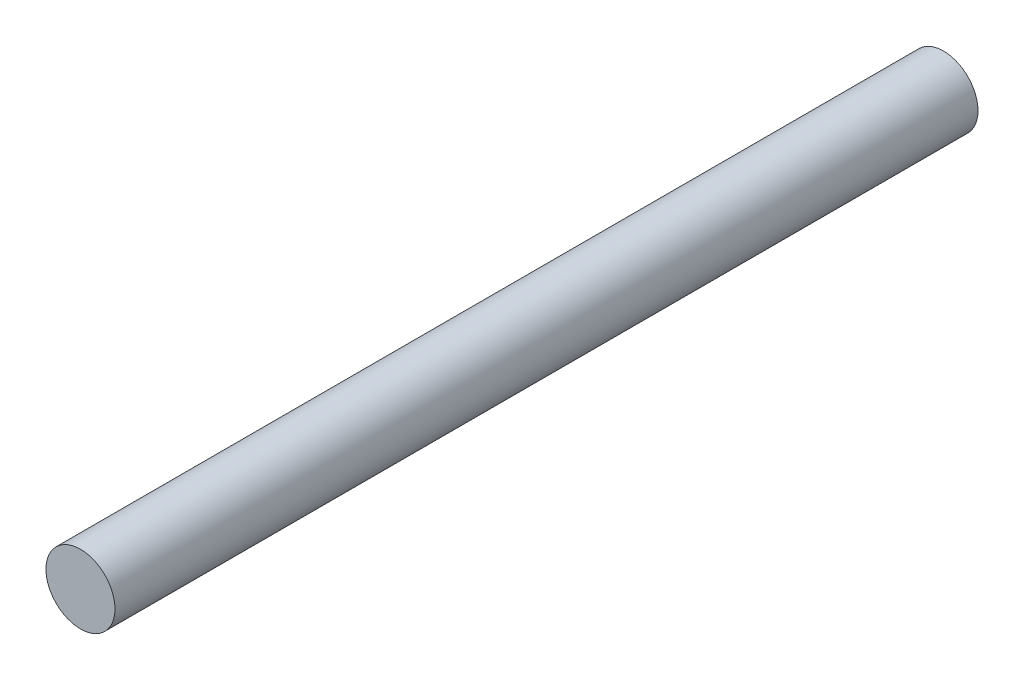
SolidWorks part; units mm, degrees
ref_plane "Alzado" through (0, 0, 0) normal (0, 0, 1) x (1, 0, 0)
ref_plane "Planta" through (0, 0, 0) normal (0, 1, 0) x (1, 0, 0)
ref_plane "Vista lateral" through (0, 0, 0) normal (1, 0, 0) x (0, 0, -1)
sketch "Croquis1" plane through (0, 0, 0) normal (0, 0, 1) x (1, 0, 0)
  circle A0 centre (0, 0) radius 1
extrude "Saliente-Extruir1" add sketch "Croquis1" along normal blind 25
